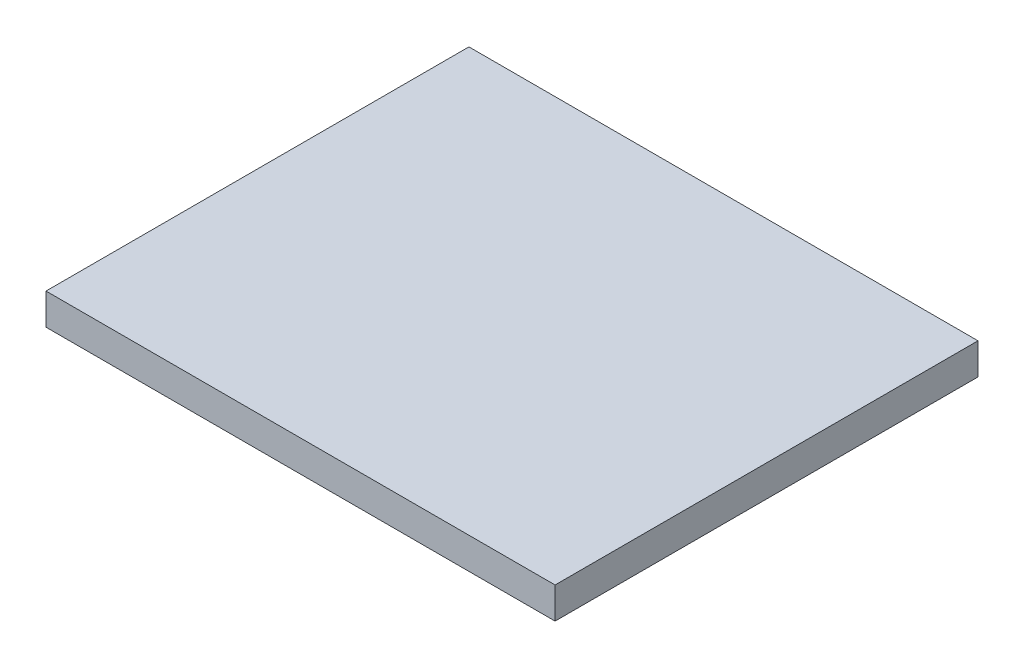
SolidWorks part; units mm, degrees
material "Plain Carbon Steel"
ref_plane "Front Plane" through (0, 0, 0) normal (0, 0, 1) x (1, 0, 0)
ref_plane "Top Plane" through (0, 0, 0) normal (0, 1, 0) x (1, 0, 0)
ref_plane "Right Plane" through (0, 0, 0) normal (1, 0, 0) x (0, 0, -1)
sketch "Sketch1" plane through (0, 0, 0) normal (0, 1, 0) x (1, 0, 0)
  line L1 (206.375, -171.45) -> (-206.375, -171.45)
  line L2 (206.375, -171.45) -> (206.375, 171.45)
  line L3 (206.375, 171.45) -> (-206.375, 171.45)
  line L4 (-206.375, -171.45) -> (-206.375, 171.45)
  line L5 (206.375, -171.45) -> (-206.375, 171.45) construction
  line L6 (206.375, 171.45) -> (-206.375, -171.45) construction
  point P0 (0, 0)
  dimension "D1" = 342.9
  dimension "D2" = 412.75
extrude "Boss-Extrude1" add sketch "Sketch1" along normal mid plane 25.4
